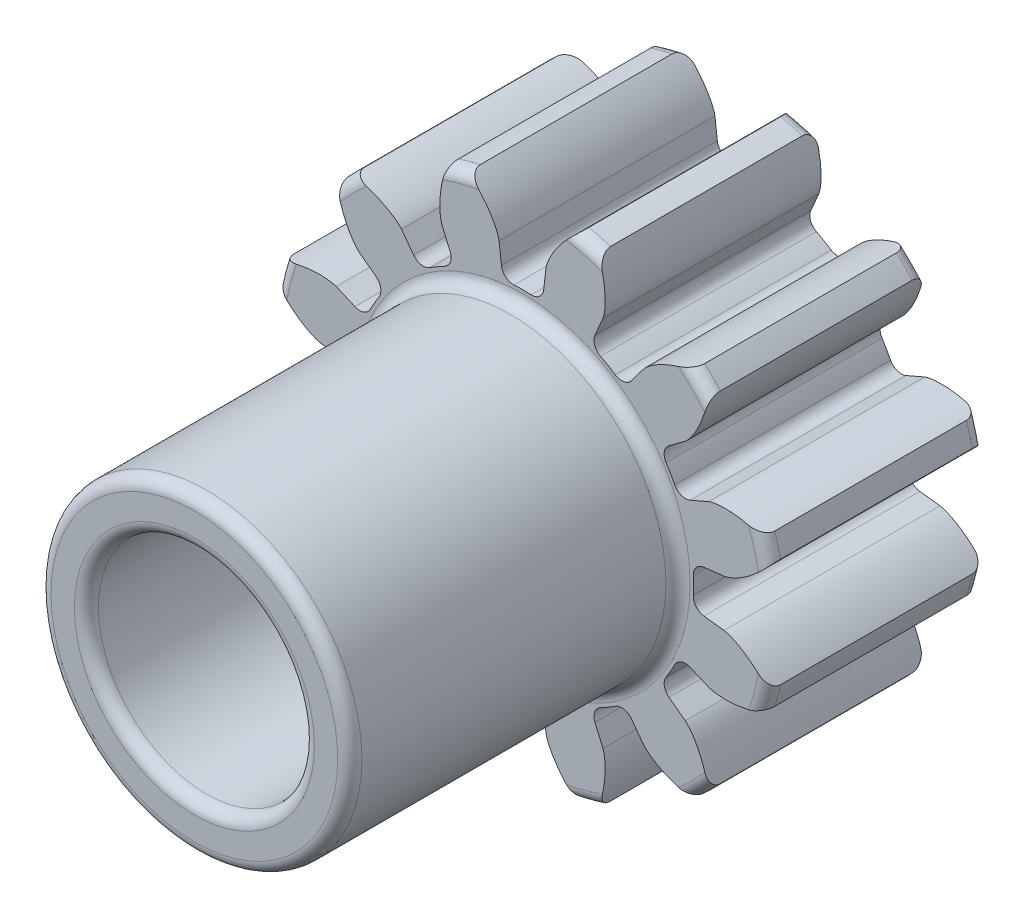
SolidWorks part; units mm, degrees
ref_plane "Front Plane" through (0, 0, 0) normal (0, 0, 1) x (1, 0, 0)
ref_plane "Top Plane" through (0, 0, 0) normal (0, 1, 0) x (1, 0, 0)
ref_plane "Right Plane" through (0, 0, 0) normal (1, 0, 0) x (0, 0, -1)
sketch "Sketch1" plane through (0, 0, 0) normal (0, 0, 1) x (1, 0, 0)
  line L0 (0, 0) -> (0, 3.175) construction
  line L1 (-1.0204, 3.5464) -> (1.0204, 2.8036) construction
  circle A0 centre (0, 0) radius 2.5135 construction
  circle A1 centre (0, 0) radius 3.7042 construction
  circle A2 centre (0, 0) radius 3.175 construction
  circle A3 centre (0, 0) radius 2.9835 construction
  circle A4 centre (0, 0) radius 1.5875 construction
  circle A5 centre (0, 0) radius 2.286 construction
  point P8 (609.6, 0)
  point P13 (152.4, 0)
  dimension "OD | Outside Diameter" = 7.4083
  dimension "Root Diameter" = 5.0271
  dimension "Gear Pitch Diameter" = 6.35
  dimension "Base Diameter" = 5.967
  dimension "For Shaft Diameter" = 3.175
  dimension "Hub Diameter" = 4.572
  dimension "Pressure Angle" = 20
  dimension "Number of Teeth" = 304.8
  dimension "Gear Pitch | Diametral Pitch" = 1219.2
sketch "Sketch2" plane through (0, 0, 0) normal (1, 0, 0) x (0, 0, -1)
  line L0 (-4.0005, 0) -> (4.0005, 0) construction
  line L1 (-4.0005, 3.7042) -> (4.0005, 3.7042) construction
  point P2 (0, 3.7042)
  point P4 (0.8255, 0)
  point P6 (0.8255, 3.7042)
  dimension "Overall Width" = 8.001
  dimension "Hub Width" = 4.826
  dimension "Face Width" = 3.175
sketch "Sketch3" plane through (0, 0, 0) normal (0, 0, 1) x (1, 0, 0)
  circle A0 centre (0, 0) radius 3.7042
  circle A1 centre (0, 0) radius 3.7042 construction
extrude "Boss-Extrude1" add sketch "Sketch3" against normal up to vertex (4.0005 mm away) and the other way up to vertex (4.0005 mm away) up to point (0, 0, -4.0005) other way up to point (0, 0, 4.0005)
sketch "Sketch5" plane through (0, 0, 0) normal (1, 0, 0) x (0, 0, -1)
  line L1 (-4.0005, 3.7042) -> (0.8255, 3.7042)
  line L2 (-4.0005, 3.7042) -> (-4.0005, 2.286)
  line L3 (-4.0005, 2.286) -> (0.8255, 2.286)
  line L4 (0.8255, 3.7042) -> (0.8255, 2.286)
  line L11 (4.0005, 1.5875) -> (-4.0005, 1.5875)
  line L12 (4.0005, 1.5875) -> (4.0005, 0)
  line L13 (4.0005, 0) -> (-4.0005, 0)
  line L14 (-4.0005, 1.5875) -> (-4.0005, 0)
  point P5 (0, 1.5875)
  point P12 (0, 2.286)
revolve "Cut-Revolve1" cut sketch "Sketch5" angle 360 about L0
fillet "Fillet2" radius 0.1775 6 edges at (3.7042, 0, -4.0005) (1.5875, 0, -4.0005) (1.5875, 0, 4.0005) (2.286, 0, -0.8255) (3.7042, 0, -0.8255) (2.286, 0, 4.0005)
sketch "Sketch4" plane through (0, 0, 0) normal (0, 0, 1) x (1, 0, 0)
  line L0 (0, 0) -> (2.4967, 0.2909) construction
  line L2 (0, 0) -> (2.4967, -0.2909) construction
  line L4 (2.4967, 0.2909) -> (2.9635, 0.3453)
  line L5 (2.9635, -0.3453) -> (2.4967, -0.2909)
  arc A0 (2.4967, 0.2909) -> (2.4967, -0.2909) centre (0, 0) cw
  arc A3 (3.6169, 0.7991) -> (3.6169, -0.7991) centre (0, 0) cw
  circle A4 centre (0, 0) radius 3.7042 construction
  spline S0 degree 4 poles (2.9635, 0.3453) (2.9647, 0.3455) (2.968, 0.346) (2.9742, 0.3471) (2.9843, 0.3493) (2.9971, 0.3526) (3.0135, 0.3574) (3.0327, 0.3637) (3.0536, 0.3714) (3.0762, 0.3805) (3.0984, 0.3902) (3.1205, 0.4005) (3.1422, 0.4114) (3.1683, 0.4252) (3.1993, 0.4426) (3.235, 0.4643) (3.2748, 0.4904) (3.3147, 0.5185) (3.3533, 0.5476) (3.3916, 0.5784) (3.4281, 0.6093) (3.4652, 0.6428) (3.4991, 0.6745) (3.536, 0.7116) (3.5656, 0.742) (3.6035, 0.7838) (3.6256, 0.8089) (3.6511, 0.8389) (3.6622, 0.8526) (3.6691, 0.861) knots 0 0 0 0 0 0.005377 0.015084 0.028532 0.04661 0.064855 0.092111 0.119476 0.146842 0.174209 0.201575 0.228941 0.256307 0.307035 0.361767 0.4165 0.471232 0.525964 0.580697 0.635429 0.690161 0.744894 0.799626 0.854358 0.909091 0.954545 1 1 1 1 1 construction
  spline S1 degree 4 poles (2.9635, 0.3453) (2.9647, 0.3455) (2.968, 0.346) (2.9742, 0.3471) (2.9843, 0.3493) (2.9971, 0.3526) (3.0135, 0.3574) (3.0327, 0.3637) (3.0536, 0.3714) (3.0762, 0.3805) (3.0984, 0.3902) (3.1205, 0.4005) (3.1422, 0.4114) (3.1683, 0.4252) (3.1993, 0.4426) (3.235, 0.4643) (3.2748, 0.4904) (3.3147, 0.5185) (3.3533, 0.5476) (3.3916, 0.5784) (3.4281, 0.6093) (3.4652, 0.6428) (3.4991, 0.6745) (3.536, 0.7116) (3.5656, 0.742) (3.5953, 0.7747) (3.6097, 0.7908) (3.6169, 0.7991) knots 0 0 0 0 0 0.005377 0.015084 0.028532 0.04661 0.064855 0.092111 0.119476 0.146842 0.174209 0.201575 0.228941 0.256307 0.307035 0.361767 0.4165 0.471232 0.525964 0.580697 0.635429 0.690161 0.744894 0.799626 0.854358 0.909091 0.909091 0.909091 0.909091 0.909091
  spline S2 degree 4 poles (2.9635, -0.3453) (2.9647, -0.3455) (2.968, -0.346) (2.9742, -0.3471) (2.9843, -0.3493) (2.9971, -0.3526) (3.0135, -0.3574) (3.0327, -0.3637) (3.0536, -0.3714) (3.0762, -0.3805) (3.0984, -0.3902) (3.1205, -0.4005) (3.1422, -0.4114) (3.1683, -0.4252) (3.1993, -0.4426) (3.235, -0.4643) (3.2748, -0.4904) (3.3147, -0.5185) (3.3533, -0.5476) (3.3916, -0.5784) (3.4281, -0.6093) (3.4652, -0.6428) (3.4991, -0.6745) (3.536, -0.7116) (3.5656, -0.742) (3.6035, -0.7838) (3.6256, -0.8089) (3.6511, -0.8389) (3.6622, -0.8526) (3.6691, -0.861) knots 0 0 0 0 0 0.005377 0.015084 0.028532 0.04661 0.064855 0.092111 0.119476 0.146842 0.174209 0.201575 0.228941 0.256307 0.307035 0.361767 0.4165 0.471232 0.525964 0.580697 0.635429 0.690161 0.744894 0.799626 0.854358 0.909091 0.954545 1 1 1 1 1 construction
  spline S3 degree 4 poles (2.9635, -0.3453) (2.9647, -0.3455) (2.968, -0.346) (2.9742, -0.3471) (2.9843, -0.3493) (2.9971, -0.3526) (3.0135, -0.3574) (3.0327, -0.3637) (3.0536, -0.3714) (3.0762, -0.3805) (3.0984, -0.3902) (3.1205, -0.4005) (3.1422, -0.4114) (3.1683, -0.4252) (3.1993, -0.4426) (3.235, -0.4643) (3.2748, -0.4904) (3.3147, -0.5185) (3.3533, -0.5476) (3.3916, -0.5784) (3.4281, -0.6093) (3.4652, -0.6428) (3.4991, -0.6745) (3.536, -0.7116) (3.5656, -0.742) (3.5953, -0.7747) (3.6097, -0.7908) (3.6169, -0.7991) knots 0 0 0 0 0 0.005377 0.015084 0.028532 0.04661 0.064855 0.092111 0.119476 0.146842 0.174209 0.201575 0.228941 0.256307 0.307035 0.361767 0.4165 0.471232 0.525964 0.580697 0.635429 0.690161 0.744894 0.799626 0.854358 0.909091 0.909091 0.909091 0.909091 0.909091
  dimension "D1" = 5.0271
extrude "Cut-Extrude1" cut sketch "Sketch4" against normal through all both and the other way through all
fillet "Fillet1" radius 0.1775 2 edges at (2.4967, -0.2909, -2.413) (2.4967, 0.2909, -2.413)
pattern_circular "CirPattern1" count 12 over 360 about axis through (0, 0, 4.0005) along (0, 0, -1) of "Cut-Extrude1", "Fillet1"
equation "\"Root Diameter@Sketch1\"=\"Root Diameter\""
equation "\"OD | Outside Diameter@Sketch1\"=\"Outside Diameter\""
equation "\"D1@CirPattern1\"=\"Number of Teeth\""
equation "\"Diametral Pitch\"= 48"
equation "\"Number of Teeth\"= 12"
equation "\"Pressure Angle\"=20"
equation "\"Pitch Diameter\"= \"Number of Teeth\" / \"Diametral Pitch\""
equation "\"Base Diameter\"= \"Pitch Diameter\" * cos ( \"Pressure Angle\" )"
equation "\"Outside Diameter\"= ( \"Number of Teeth\" + 2 ) / \"Diametral Pitch\""
equation "\"Dedendum\"= 1.25 / \"Diametral Pitch\""
equation "\"Root Diameter\"= \"Pitch Diameter\" - ( 2 * \"Dedendum\" )"
equation "\"Pitch Angle\"= 360deg / \"Number of Teeth\""
equation "\"Alpha\"= sqr ( \"Pitch Diameter\" ^ 2 - \"Base Diameter\" ^ 2 ) / \"Base Diameter\" * 180 / PI - \"Pressure Angle\""
equation "\"Beta\"= ( \"Pitch Angle\" / 4 - \"Alpha\" )"
equation "\"Phi\"= sqr ( ( \"Outside Diameter\" / 2 ) ^ 2 - ( \"Base Diameter\" / 2 ) ^ 2 ) / ( \"Base Diameter\" / 2 )"
equation "\"Addendum\"= 1 / \"Diametral Pitch\""
equation "\"WorkingDepth\"= 2 / \"Diametral Pitch\""
equation "\"WholeDepth\"= 2.25 / \"Diametral Pitch\""
equation "\"Clearance\"= 0.25 / \"Diametral Pitch\""
equation "\"ToothThickness\"= ( pi * 2 ) / \"Diametral Pitch\""
equation "\"CircularPitch\"= pi / \"Diametral Pitch\""
equation "\"Number of Teeth@Sketch1\"=\"Number of Teeth\""
equation "\"Gear Pitch | Diametral Pitch@Sketch1\"=\"Diametral Pitch\""
equation "\"Pressure Angle@Sketch1\"=\"Pressure Angle\""
equation "\"Gear Pitch Diameter@Sketch1\"=\"Pitch Diameter\""
equation "\"Base Diameter@Sketch1\"=\"Base Diameter\""
equation "\"Fillet\"= \"Clearance\" * cos ( \"Pressure Angle\" ) * tan ( ( 90 + \"Pressure Angle\" ) / 2 )"
equation "\"D1@Fillet1\"=\"Fillet\""
equation "\"D1@Sketch4\"=if( \"Base Diameter\">\"Root Diameter\",\"Root Diameter\",\"Base Diameter\"-.00001)"
equation "\"D1@Fillet2\"=\"Fillet\""
